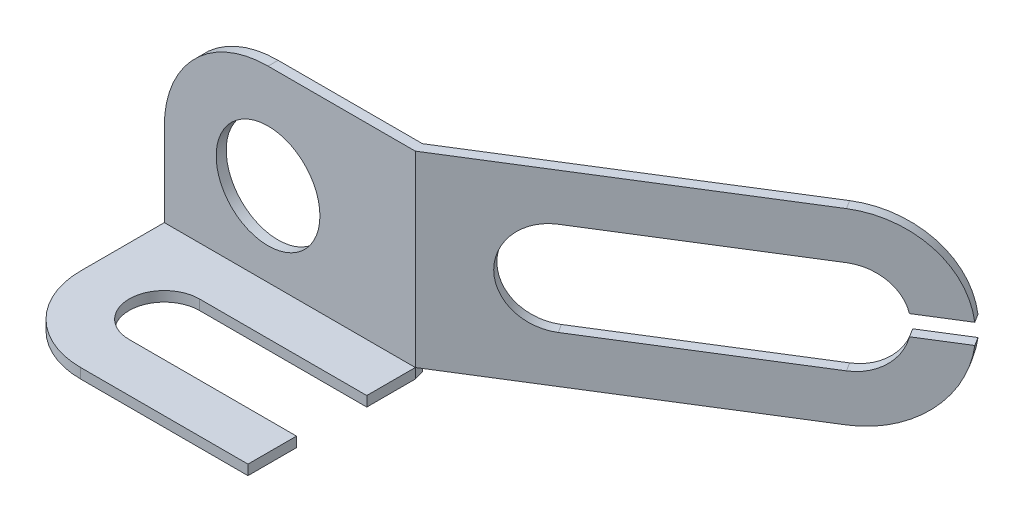
SolidWorks part; units mm, degrees
ref_plane "Front Plane" through (0, 0, 0) normal (0, 0, 1) x (1, 0, 0)
ref_plane "Top Plane" through (0, 0, 0) normal (0, 1, 0) x (1, 0, 0)
ref_plane "Right Plane" through (0, 0, 0) normal (1, 0, 0) x (0, 0, -1)
sketch "Sketch1" plane through (0, 0, 0) normal (0, 1, 0) x (1, 0, 0)
  line L0 (0, 0) -> (-38.1, 0)
  line L1 (-38.1, 0) -> (-38.1, -12.7)
  line L2 (-25.4, -25.4) -> (0, -25.4)
  line L3 (0, -25.4) -> (0, -18.034)
  line L4 (0, -18.034) -> (-25.4, -18.034)
  line L5 (-25.4, -7.366) -> (0, -7.366)
  line L6 (0, -7.366) -> (0, 0)
  arc A0 (-25.4, -7.366) -> (-25.4, -18.034) centre (-25.4, -12.7) ccw
  arc A1 (-25.4, -25.4) -> (-38.1, -12.7) centre (-25.4, -12.7) cw
  dimension "D3" = 10.668
  dimension "D6" = 12.7
  dimension "D1" = 7.366
  dimension "D2" = 7.366
  dimension "D4" = 25.4
  dimension "D5" = 38.1
extrude "Boss-Extrude1" add sketch "Sketch1" along normal blind 1.524
sketch "Sketch2" plane through (0, 0, 0) normal (0, 0, 1) x (1, 0, 0)
  line L0 (0, 0) -> (0, 29.972)
  line L1 (0, 29.972) -> (-22.352, 29.972)
  line L5 (-38.1, 14.224) -> (-38.1, 0)
  line L6 (0, 0) -> (-38.1, 0)
  arc A0 (-22.352, 29.972) -> (-38.1, 14.224) centre (-22.352, 14.224) ccw
  circle A1 centre (-22.352, 14.224) radius 7.874
  dimension "D1" = 15.748
  dimension "D4" = 15.748
  dimension "D2" = 22.352
  dimension "D3" = 14.224
extrude "Boss-Extrude2" add sketch "Sketch2" against normal blind 1.524
ref_plane "Plane1" through (0, 0, 0) normal (0.5299, 0, 0.848) x (0, 1, 0)
sketch "Sketch3" plane through (0, 0, 0) normal (0.5299, 0, 0.848) x (0, 1, 0)
  line L0 (29.972, 0) -> (29.972, -47.498)
  line L1 (1.524, -47.498) -> (1.524, 0)
  line L2 (1.524, 0) -> (29.972, 0) construction
  line L3 (22.86, -15.748) -> (22.86, -47.498)
  line L4 (8.636, -15.748) -> (8.636, -47.498)
  line L5 (29.972, 0) -> (1.524, 0)
  line L6 (17.272, -54.4448) -> (17.272, -61.6401)
  line L7 (14.224, -54.4448) -> (14.224, -61.6401)
  arc A0 (29.972, -47.498) -> (17.272, -61.6401) centre (15.748, -47.498) cw
  arc A1 (8.636, -47.498) -> (14.224, -54.4448) centre (15.748, -47.498) ccw
  arc A2 (22.86, -15.748) -> (8.636, -15.748) centre (15.748, -15.748) ccw
  arc A3 (14.224, -61.6401) -> (1.524, -47.498) centre (15.748, -47.498) cw
  arc A4 (17.272, -54.4448) -> (22.86, -47.498) centre (15.748, -47.498) ccw
  point P14 (15.748, 0)
  dimension "D1" = 14.224
  dimension "D2" = 31.75
  dimension "D3" = 15.748
  dimension "D4" = 3.048
extrude "Boss-Extrude3" add sketch "Sketch3" against normal blind 1.524
sketch "Sketch4" plane through (0, 0, 0) normal (0, -1, 0) x (1, 0, 0)
  line L0 (0, 0) -> (-0.437, -1.524)
  line L1 (-38.1, -1.524) -> (0, -1.524) construction
  line L2 (-0.437, -1.524) -> (0, -1.524)
  line L3 (0, 7.366) -> (0, -1.524) construction
  line L4 (0, -1.524) -> (0, 0)
  line L5 (-0.437, -1.524) -> (39.473, -26.4625) construction
extrude "Cut-Extrude1" cut sketch "Sketch4" against normal up to surface (1.524 mm away) up to face at (15.8633, 1.524, -10.9361)
